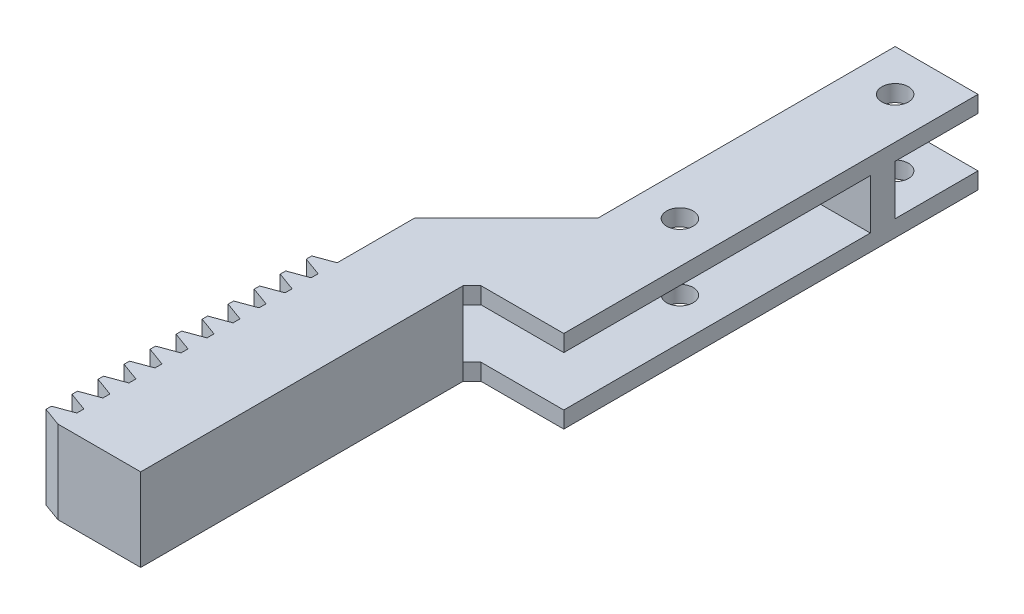
SolidWorks part; units mm, degrees
ref_plane "前视基准面" through (0, 0, 0) normal (0, 0, 1) x (1, 0, 0)
ref_plane "上视基准面" through (0, 0, 0) normal (0, 1, 0) x (1, 0, 0)
ref_plane "右视基准面" through (0, 0, 0) normal (1, 0, 0) x (0, 0, -1)
sketch "草图1" plane through (0, 0, 0) normal (0, 1, 0) x (1, 0, 0)
  line L1 (-5, -25) -> (5, -25)
  line L2 (-5, -25) -> (-5, 25)
  line L3 (-5, 25) -> (5, 25)
  line L4 (5, -25) -> (5, 25)
  line L5 (-5, -25) -> (5, 25) construction
  line L6 (-5, 25) -> (5, -25) construction
  point P0 (0, 0)
  dimension "D1" = 10
  dimension "D2" = 50
extrude "凸台-拉伸1" add sketch "草图1" along normal blind 2
sketch "草图2" plane through (0, 2, 0) normal (0, 1, 0) x (1, 0, 0)
  line L0 (0, 22.9854) -> (0, -13.3669) construction
  line L1 (5, 25) -> (-5, 25) construction
  circle A0 centre (0, 20) radius 1.6
  circle A3 centre (0, -5.9807) radius 1.6
  dimension "D1" = 3.2
  dimension "D2" = 5
  dimension "D3" = 25.9808
extrude "切除-拉伸1" cut sketch "草图2" against normal up to next
sketch "草图8" plane through (0, 2, 0) normal (0, 1, 0) x (1, 0, 0)
  line L0 (-5, -25) -> (-6.07, -26.07)
  line L1 (-6.07, -26.07) -> (-6.07, -65)
  line L2 (-6.07, -65) -> (-16.07, -65)
  line L3 (-16.07, -65) -> (-16.07, -21.9279)
  line L4 (-16.07, -21.9279) -> (-5, -10.8579)
  line L5 (-5, 25) -> (-5, -25) construction
  line L6 (-5, -10.8579) -> (-5, -25)
  line L8 (-5, -25) -> (5, -25) construction
  dimension "D1" = 10
  dimension "D2" = 10
  dimension "D3" = 45
  dimension "D4" = 40
  dimension "D5" = 11.07
extrude "凸台-拉伸5" add sketch "草图8" against normal up to surface (2 mm away) up to face at (0, 0, -21.6)
sketch "草图4" plane through (0, 2, 0) normal (0, 1, 0) x (1, 0, 0)
  line L0 (0, 15.9837) -> (0, 0) construction
  line L1 (5, -25) -> (5, 25) construction
  line L2 (-5, 12) -> (5, 12)
  line L3 (-5, 12) -> (-5, 15)
  line L4 (-5, 15) -> (5, 15)
  line L5 (5, 12) -> (5, 15)
  line L6 (-5, 12) -> (5, 15) construction
  line L7 (-5, 15) -> (5, 12) construction
  line L13 (-6.07, -26.07) -> (-13.1411, -18.9989)
  line L14 (-5, -10.8579) -> (-16.07, -21.9279) construction
  line L15 (-16.07, -65) -> (-6.07, -65) construction
  line L17 (-6.07, -65) -> (-6.07, -26.07) construction
  line L18 (-16.07, -21.9279) -> (-16.07, -65) construction
  line L19 (-16.07, -65) -> (-6.07, -65)
  line L21 (-6.07, -65) -> (-6.07, -26.07)
  line L22 (-16.07, -21.9279) -> (-16.07, -65)
  line L23 (-13.1411, -18.9989) -> (-16.07, -21.9279)
  circle A0 centre (0, 20) radius 1.6 construction
  point P3 (0, 13.5)
  dimension "D1" = 3
  dimension "D2" = 8
extrude "凸台-拉伸2" add sketch "草图4" along normal blind 6
sketch "草图5" plane through (0, 8, 0) normal (0, 1, 0) x (1, 0, 0)
  line L9 (-5, 25) -> (-5, -10.8579)
  line L10 (-5, -10.8579) -> (-16.07, -21.9279)
  line L11 (-16.07, -21.9279) -> (-16.07, -65)
  line L12 (-16.07, -65) -> (-6.07, -65)
  line L13 (-6.07, -65) -> (-6.07, -26.07)
  line L15 (5, -25) -> (5, 25)
  line L16 (5, 25) -> (-5, 25)
  line L17 (-13.1411, -18.9989) -> (-16.07, -21.9279) construction
  line L18 (-6.07, -26.07) -> (-5, -25)
  line L19 (-5, -25) -> (5, -25)
  circle A0 centre (0, -5.9807) radius 1.6 construction
  circle A1 centre (0, 20) radius 1.6 construction
  circle A2 centre (0, -5.9807) radius 1.6
  circle A3 centre (0, 20) radius 1.6
extrude "凸台-拉伸3" add sketch "草图5" along normal blind 2
sketch "草图7" plane through (0, 10, 0) normal (0, 1, 0) x (1, 0, 0)
  line L0 (0, -4.5264) -> (0, -45.0373) construction
  line L1 (-16.07, -65) -> (-18.32, -64.1811)
  line L2 (-18.32, -64.1811) -> (-18.32, -63.5202)
  line L3 (-18.32, -63.8506) -> (-16.07, -63.8506) construction
  line L4 (-17.07, -64.636) -> (-17.07, -63.0652) construction
  line L6 (-16.07, -62.7013) -> (-18.32, -63.5202)
  line L7 (-16.07, -62.7013) -> (-16.07, -65)
  dimension "D1" = 70
  dimension "D2" = 1
  dimension "D3" = 2.25
  dimension "D4" = 1.5708
extrude "凸台-拉伸4" add sketch "草图7" against normal up to surface (10 mm away) up to face at (0, 0, -21.6)
pattern_linear "阵列(线性)1" count 11 spacing 3.1416 along (0, 0, -1) of "凸台-拉伸4"
